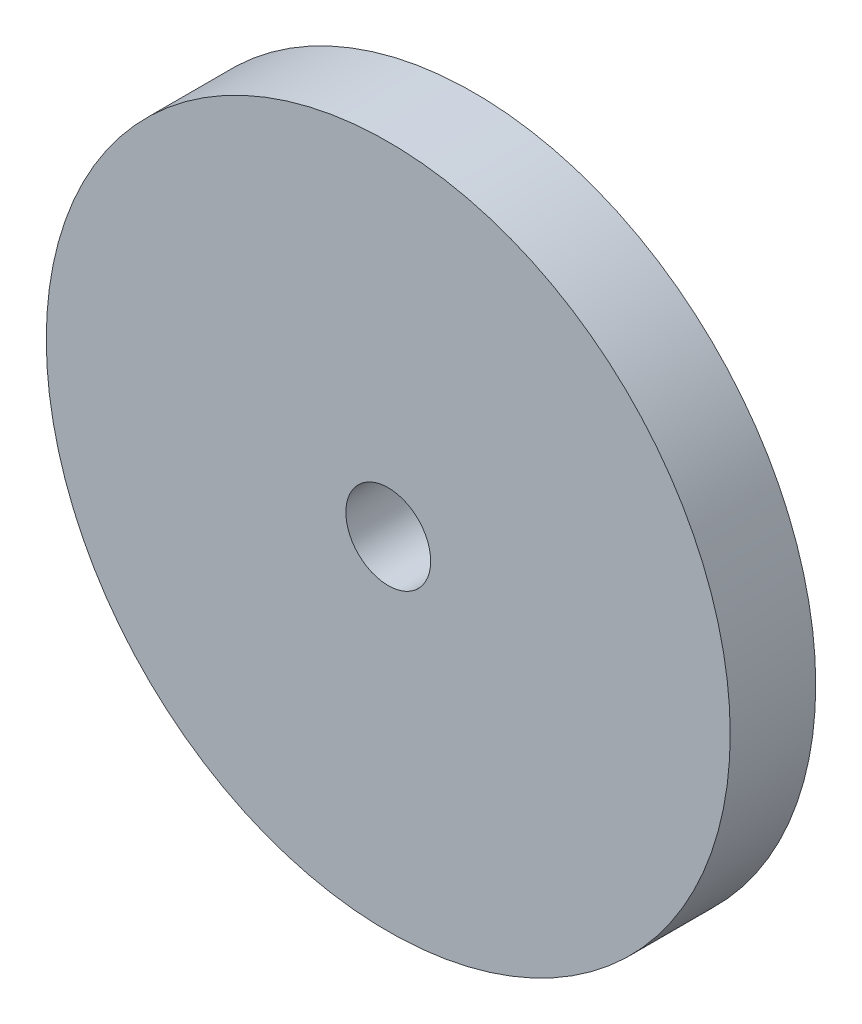
SolidWorks part; units mm, degrees
material "Pine"
ref_plane "Front Plane" through (0, 0, 0) normal (0, 0, 1) x (1, 0, 0)
ref_plane "Top Plane" through (0, 0, 0) normal (0, 1, 0) x (1, 0, 0)
ref_plane "Right Plane" through (0, 0, 0) normal (1, 0, 0) x (0, 0, -1)
sketch "Sketch1" plane through (0, 0, 0) normal (0, 0, 1) x (1, 0, 0)
  circle A0 centre (0, 0) radius 3.1496
  circle A1 centre (0, 0) radius 25.4
  dimension "D1" = 6.2992
  dimension "D2" = 50.8
extrude "Boss-Extrude1" add sketch "Sketch1" along normal blind 6.35
